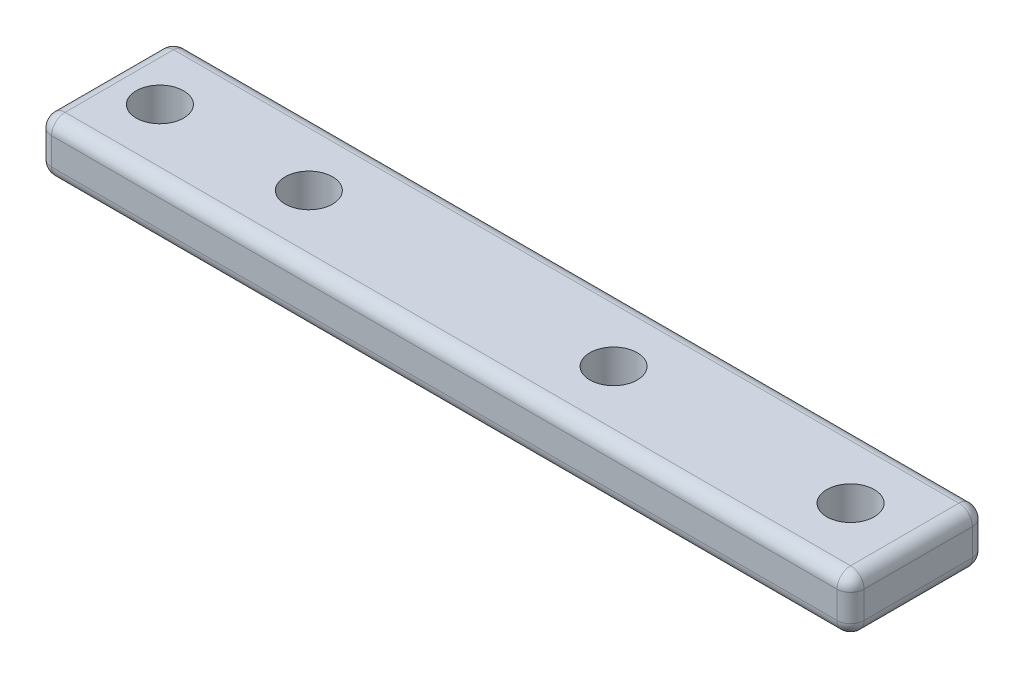
SolidWorks part; units mm, degrees
ref_plane "Front Plane" through (0, 0, 0) normal (0, 0, 1) x (1, 0, 0)
ref_plane "Top Plane" through (0, 0, 0) normal (0, 1, 0) x (1, 0, 0)
ref_plane "Right Plane" through (0, 0, 0) normal (1, 0, 0) x (0, 0, -1)
sketch "Sketch1" plane through (0, 0, 0) normal (0, 1, 0) x (1, 0, 0)
  line L1 (-30, 5) -> (30, 5)
  line L2 (-30, 5) -> (-30, -5)
  line L3 (-30, -5) -> (30, -5)
  line L4 (30, 5) -> (30, -5)
  line L5 (-30, 5) -> (30, -5) construction
  line L6 (-30, -5) -> (30, 5) construction
  point P1 (0, 0)
  dimension "D1" = 60
  dimension "D2" = 10
extrude "Boss-Extrude1" add sketch "Sketch1" along normal blind 4
sketch "Sketch2" plane through (0, 4, 0) normal (0, 1, 0) x (1, 0, 0)
  line L0 (30, -5) -> (30, 5) construction
  line L1 (-30, 5) -> (-30, -5) construction
  line L2 (30, 5) -> (-30, 5) construction
  circle A0 centre (-26, 0) radius 1.75
  circle A1 centre (7.5, 0) radius 1.75
  circle A2 centre (25, 0) radius 1.75
  circle A3 centre (-15, 0) radius 1.75
  dimension "D1" = 3.5
  dimension "D2" = 3.5
  dimension "D3" = 3.5
  dimension "D11" = 15
  dimension "D12" = 3.5
  dimension "D4" = 5
  dimension "D5" = 4
  dimension "D6" = 37.5
  dimension "D7" = 5
  dimension "D8" = 5
  dimension "D9" = 5
  dimension "D10" = 22.5
extrude "Cut-Extrude1" cut sketch "Sketch2" against normal blind 4
fillet "Fillet1" radius 1 12 edges at (30, 4, 0) (30, 0, 0) (-30, 4, 0) (-30, 0, 0) (30, 2, -5) (0, 4, -5) (-30, 2, -5) (0, 0, -5) (-30, 2, 5) (0, 4, 5) (30, 2, 5) (0, 0, 5)
